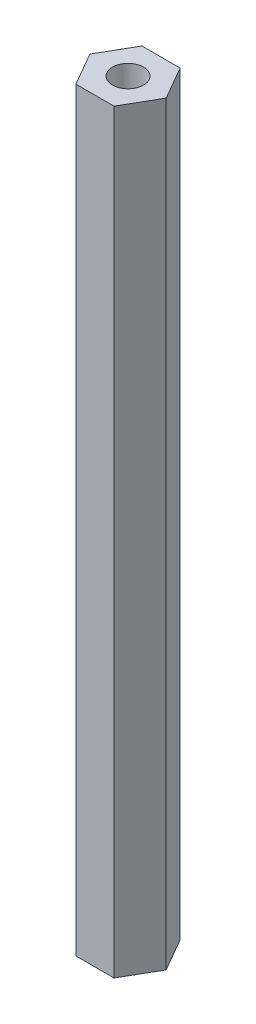
SolidWorks part; units mm, degrees
ref_plane "Alzado" through (0, 0, 0) normal (0, 0, 1) x (1, 0, 0)
ref_plane "Planta" through (0, 0, 0) normal (0, 1, 0) x (1, 0, 0)
ref_plane "Vista lateral" through (0, 0, 0) normal (1, 0, 0) x (0, 0, -1)
sketch "Croquis1" plane through (0, 0, 0) normal (0, 1, 0) x (1, 0, 0)
  line L1 (-2.0207, 3.5) -> (-4.0415, 0)
  line L2 (-4.0415, 0) -> (-2.0207, -3.5)
  line L3 (-2.0207, -3.5) -> (2.0207, -3.5)
  line L4 (2.0207, -3.5) -> (4.0415, 0)
  line L5 (4.0415, 0) -> (2.0207, 3.5)
  line L6 (2.0207, 3.5) -> (-2.0207, 3.5)
  circle A0 centre (0, 0) radius 3.5 construction
  dimension "D1" = 7
extrude "Saliente-Extruir1" add sketch "Croquis1" along normal mid plane 80
sketch "Croquis2" plane through (0, 40, 0) normal (0, 1, 0) x (1, 0, 0)
  point P0 (0, 0)
hole_wizard "Taladro roscado M41" positions "Croquis3" profile "Croquis4" tap size "M4" standard "ISO"
sketch "Croquis3" plane through (0, 40, 0) normal (0, 1, 0) x (1, 0, 0)
  point P0 (0, 0)
sketch "Croquis4" plane through (0, 40, 0) normal (1, 0, 0) x (0, 0, 1)
  line L0 (0, 0) -> (0, 13.4914)
  line L1 (0, 13.4914) -> (1.65, 12.5)
  line L2 (1.65, 12.5) -> (1.65, 0)
  line L5 (1.65, 0) -> (0, 0)
  line L10 (0, 13.4914) -> (-1.65, 12.5) construction
  line L11 (0, -6.35) -> (0, 107.95) construction
  dimension "Diámetro de perforador para roscar" = 3.3
  dimension "Profundidad de perforador para roscar" = 12.5
  dimension "Ángulo de perforador" = 118
cosmetic thread "Rosca de taladro1" parameters "D1"=10, "D2"=4
mirror "Simetría1" about plane through (0, 0, 0) normal (0, 1, 0) of "Taladro roscado M41"
cosmetic thread "Rosca de taladro3" parameters "D1"=10, "D2"=4
